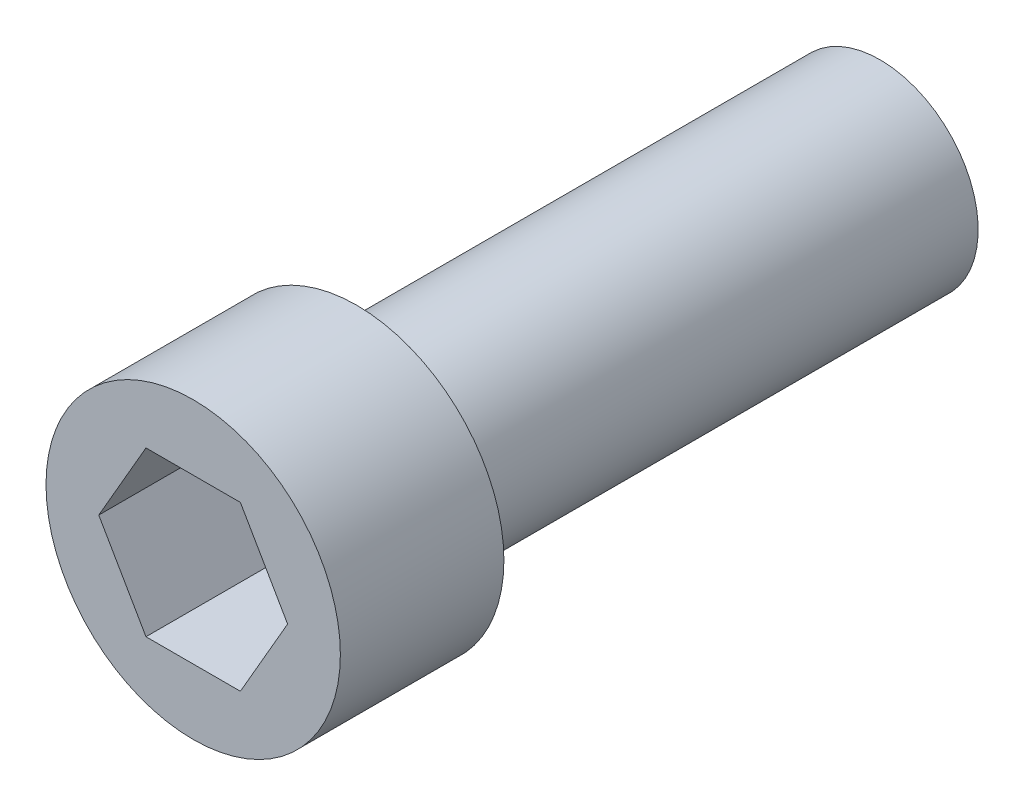
SolidWorks part; units mm, degrees
ref_plane "Front Plane" through (0, 0, 0) normal (0, 0, 1) x (1, 0, 0)
ref_plane "Top Plane" through (0, 0, 0) normal (0, 1, 0) x (1, 0, 0)
ref_plane "Right Plane" through (0, 0, 0) normal (1, 0, 0) x (0, 0, -1)
sketch "Sketch1" plane through (0, 0, 0) normal (0, 0, 1) x (1, 0, 0)
  circle A0 centre (0, 0) radius 2.25
  dimension "D1" = 4.5
extrude "Boss-Extrude1" add sketch "Sketch1" along normal blind 2.5
sketch "Sketch2" plane through (0, 0, 2.5) normal (0, 0, 1) x (1, 0, 0)
  line L1 (1.4434, 0) -> (0.7217, 1.25)
  line L2 (0.7217, 1.25) -> (-0.7217, 1.25)
  line L3 (-0.7217, 1.25) -> (-1.4434, 0)
  line L4 (-1.4434, 0) -> (-0.7217, -1.25)
  line L5 (-0.7217, -1.25) -> (0.7217, -1.25)
  line L6 (0.7217, -1.25) -> (1.4434, 0)
  circle A0 centre (0, 0) radius 1.25 construction
  dimension "D1" = 2.5
extrude "Cut-Extrude1" cut sketch "Sketch2" against normal blind 2
sketch "Sketch3" plane through (0, 0, 0) normal (0, 0, -1) x (-1, 0, 0)
  circle A0 centre (0, 0) radius 1.5
  dimension "D1" = 3
extrude "Boss-Extrude2" add sketch "Sketch3" along normal blind 8
